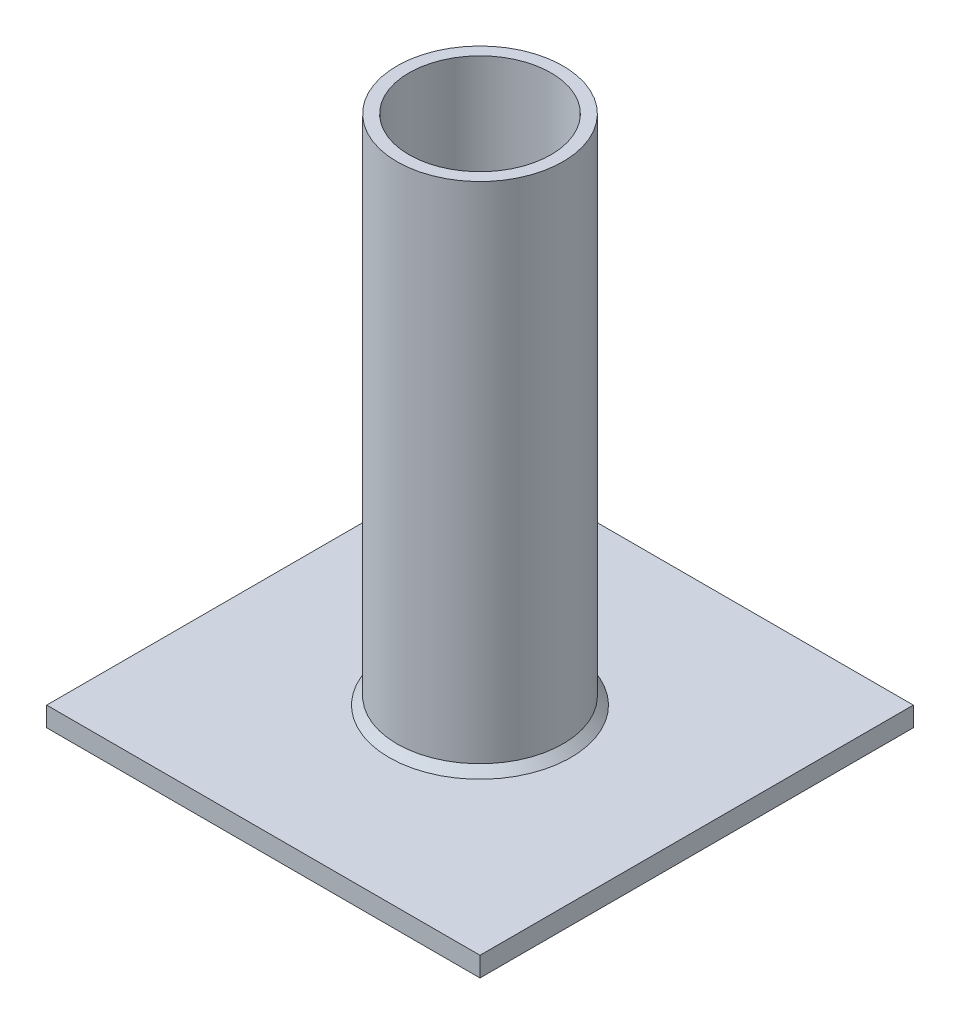
SolidWorks part; units mm, degrees
ref_plane "Plano frontal" through (0, 0, 0) normal (0, 0, 1) x (1, 0, 0)
ref_plane "Plano superior" through (0, 0, 0) normal (0, 1, 0) x (1, 0, 0)
ref_plane "Plano direito" through (0, 0, 0) normal (1, 0, 0) x (0, 0, -1)
sketch "Sketch1" plane through (0, 0, 0) normal (0, 1, 0) x (1, 0, 0)
  line L1 (-55, 55) -> (55, 55)
  line L2 (-55, 55) -> (-55, -55)
  line L3 (-55, -55) -> (55, -55)
  line L4 (55, 55) -> (55, -55)
  line L5 (-55, 55) -> (55, -55) construction
  line L6 (-55, -55) -> (55, 55) construction
  point P0 (0, 0)
extrude "Boss-Extrude1" add sketch "Sketch1" along normal blind 5
sketch "Sketch2" plane through (0, 5, 0) normal (0, 1, 0) x (1, 0, 0)
  circle A0 centre (0, 0) radius 18.025
  circle A1 centre (0, 0) radius 21.075
  dimension "D1" = 3.05
extrude "Boss-Extrude2" add sketch "Sketch2" along normal blind 130
chamfer "Chamfer1" distance 2 angle 45 1 edges at (0, 5, 21.075)
